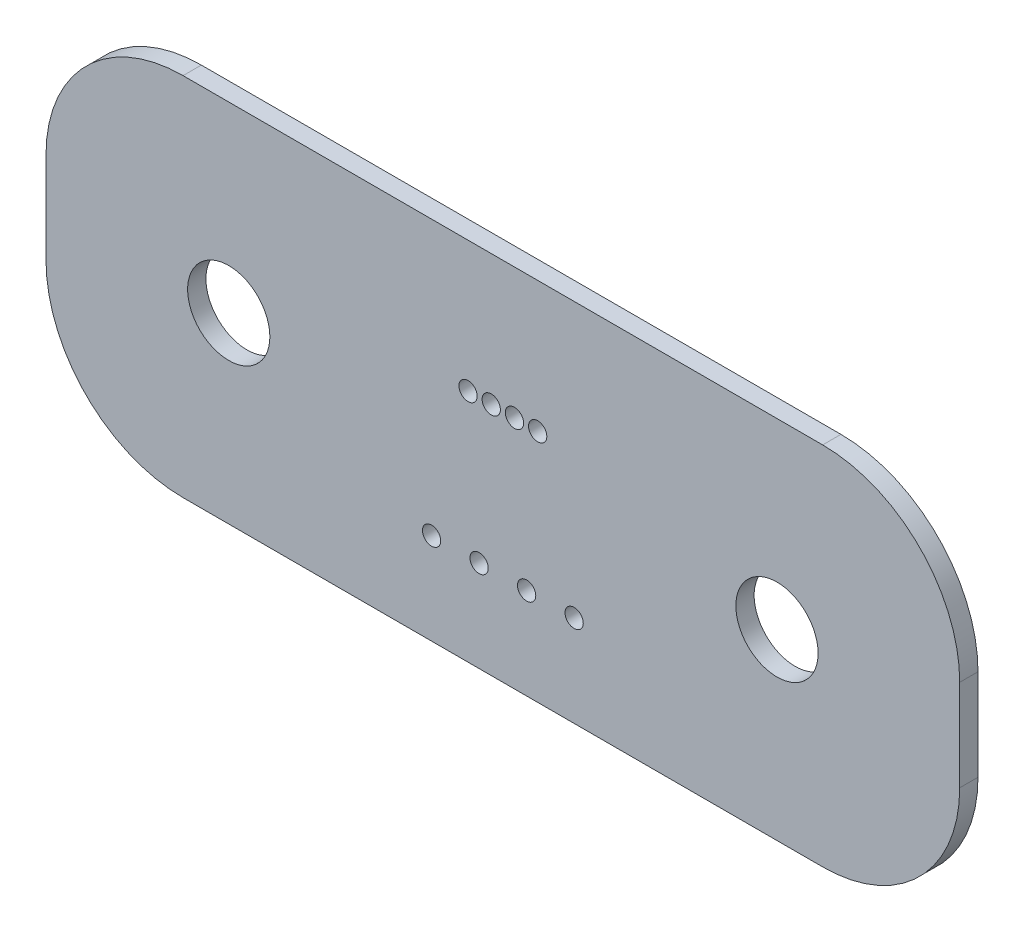
SolidWorks part; units mm, degrees
ref_plane "Front Plane" through (0, 0, 0) normal (0, 0, 1) x (1, 0, 0)
ref_plane "Top Plane" through (0, 0, 0) normal (0, 1, 0) x (1, 0, 0)
ref_plane "Right Plane" through (0, 0, 0) normal (1, 0, 0) x (0, 0, -1)
sketch "Sketch1" plane through (0, 0, 0) normal (0, 0, 1) x (1, 0, 0)
  line L0 (-17.5, -5) -> (17.5, -5)
  line L2 (-25, -17.5) -> (-25, -12.5)
  line L4 (25, -17.5) -> (25, -12.5)
  line L5 (-17.5, -25) -> (17.5, -25)
  line L6 (-1.905, -12.15) -> (1.905, -12.15) construction
  line L7 (0, 0) -> (0, -12.15) construction
  line L8 (-3.9, -20) -> (3.9, -20) construction
  line L9 (0, -12.15) -> (0, -25) construction
  circle A2 centre (15, -15) radius 2.25
  circle A3 centre (-15, -15) radius 2.25
  circle A9 centre (-1.905, -12.15) radius 0.5
  circle A10 centre (1.905, -12.15) radius 0.5
  circle A11 centre (-0.635, -12.15) radius 0.5
  circle A12 centre (0.635, -12.15) radius 0.5
  arc A13 (-17.5, -5) -> (-25, -12.5) centre (-17.5, -12.5) ccw
  arc A14 (17.5, -5) -> (25, -12.5) centre (17.5, -12.5) cw
  arc A15 (-17.5, -25) -> (-25, -17.5) centre (-17.5, -17.5) cw
  arc A16 (17.5, -25) -> (25, -17.5) centre (17.5, -17.5) ccw
  circle A17 centre (-3.9, -20) radius 0.5
  circle A18 centre (-1.3, -20) radius 0.5
  circle A19 centre (1.3, -20) radius 0.5
  circle A20 centre (3.9, -20) radius 0.5
  point P0 (0, 0)
  point P14 (0, -12.15)
  point P37 (0, -20)
  dimension "D6" = 25
  dimension "D7" = 10
  dimension "D8" = 10
  dimension "D9" = 12.15
  dimension "D4" = 4.5
  dimension "D13" = 1
  dimension "D15" = 7.5
  dimension "D16" = 7.5
  dimension "D17" = 7.5
  dimension "D18" = 1
  dimension "D1" = 10
  dimension "D2" = 10
  dimension "D3" = 15
  dimension "D5" = 25
  dimension "D10" = 3.81
  dimension "D11" = 1.27
  dimension "D12" = 1.27
  dimension "D14" = 20
  dimension "D19" = 2.6
  dimension "D20" = 2.6
  dimension "D21" = 2.6
  dimension "D22" = 5
extrude "Boss-Extrude1" add sketch "Sketch1" along normal blind 1
